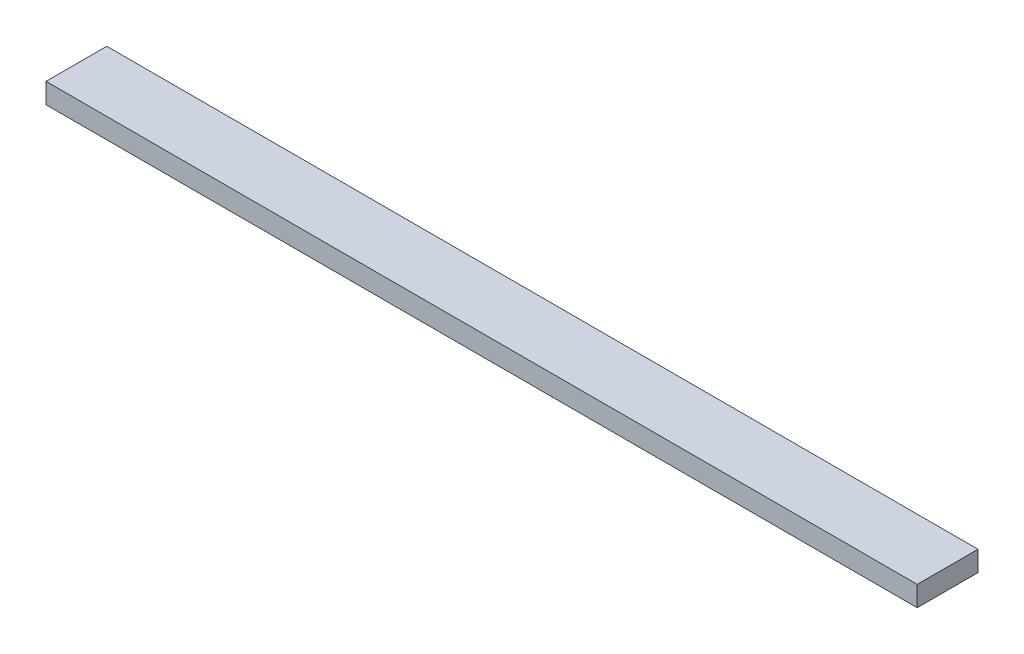
SolidWorks part; units mm, degrees
ref_plane "Front Plane" through (0, 0, 0) normal (0, 0, 1) x (1, 0, 0)
ref_plane "Top Plane" through (0, 0, 0) normal (0, 1, 0) x (1, 0, 0)
ref_plane "Right Plane" through (0, 0, 0) normal (1, 0, 0) x (0, 0, -1)
sketch "Sketch1" plane through (0, 0, 0) normal (0, 1, 0) x (1, 0, 0)
  line L1 (0, 0) -> (546.1, 0)
  line L2 (0, 0) -> (0, 38.1)
  line L3 (0, 38.1) -> (546.1, 38.1)
  line L4 (546.1, 0) -> (546.1, 38.1)
  dimension "D1" = 546.1
  dimension "D2" = 38.1
extrude "Boss-Extrude1" add sketch "Sketch1" along normal blind 12.7
